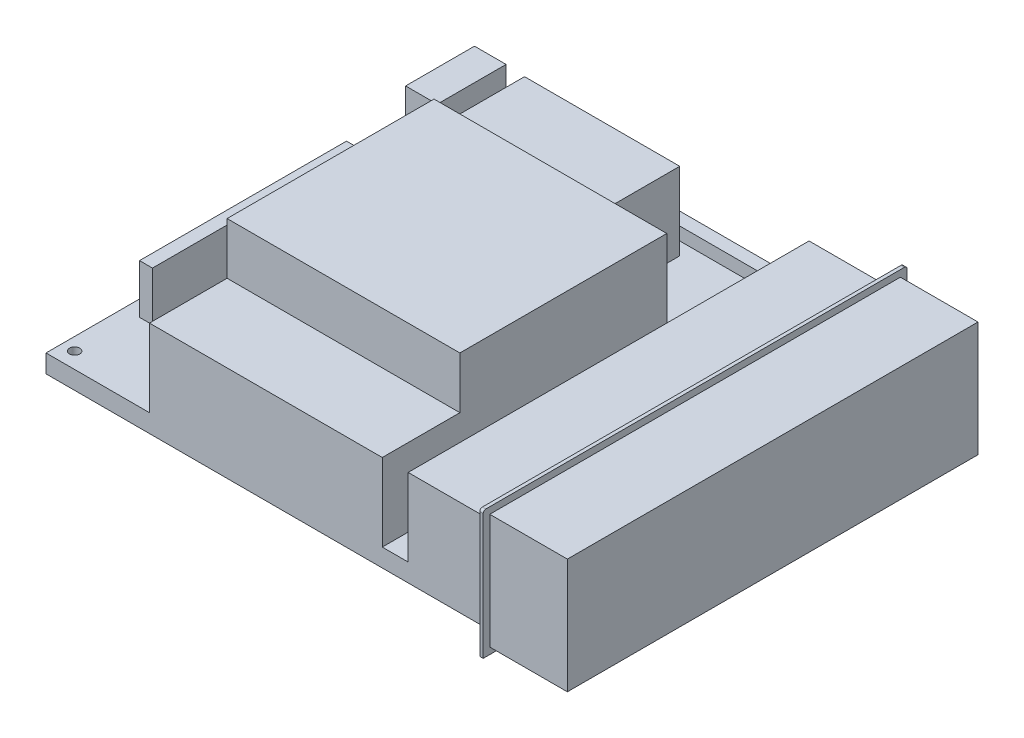
SolidWorks part; units mm, degrees
ref_plane "Front Plane" through (0, 0, 0) normal (0, 0, 1) x (1, 0, 0)
ref_plane "Top Plane" through (0, 0, 0) normal (0, 1, 0) x (1, 0, 0)
ref_plane "Right Plane" through (0, 0, 0) normal (1, 0, 0) x (0, 0, -1)
sketch "Sketch1" plane through (0, 0, 0) normal (0, 1, 0) x (1, 0, 0)
  line L1 (-85, -85) -> (85, -85)
  line L2 (-85, -85) -> (-85, 85)
  line L3 (-85, 85) -> (85, 85)
  line L4 (85, -85) -> (85, 85)
  line L5 (-85, -85) -> (85, 85) construction
  line L6 (-85, 85) -> (85, -85) construction
  point P0 (0, 0)
  dimension "D1" = 170
extrude "alusplaat" add sketch "Sketch1" along normal blind 2
sketch "Sketch2" plane through (0, 2, 0) normal (0, 1, 0) x (-1, 0, 0)
  line L1 (-85, 85) -> (-55, 85)
  line L2 (-85, 85) -> (-85, -70)
  line L3 (-85, -70) -> (-55, -70)
  line L4 (-55, 85) -> (-55, -70)
  dimension "D1" = 155
  dimension "D2" = 30
extrude "pistikud" add sketch "Sketch2" along normal blind 35
sketch "Sketch3" plane through (0, 2, 0) normal (0, 1, 0) x (1, 0, 0)
  line L0 (-85, -85) -> (55, -85) construction
  line L1 (-45, -85) -> (45, -85)
  line L2 (-45, -85) -> (-45, 25)
  line L3 (-45, 25) -> (45, 25)
  line L4 (45, -85) -> (45, 25)
  line L5 (-85, 85) -> (-85, -85) construction
  dimension "D1" = 90
  dimension "D2" = 40
  dimension "D3" = 110
extrude "cpu+mälud" add sketch "Sketch3" along normal blind 55
sketch "Sketch4" plane through (0, 2, 0) normal (0, 1, 0) x (1, 0, 0)
  line L1 (5, 35) -> (-55, 35)
  line L2 (5, 35) -> (5, 70)
  line L3 (5, 70) -> (-55, 70)
  line L4 (-55, 35) -> (-55, 70)
  line L5 (-85, 85) -> (-85, -85) construction
  line L6 (85, 85) -> (-85, 85) construction
  dimension "D1" = 35
  dimension "D2" = 60
  dimension "D3" = 30
  dimension "D4" = 15
extrude "sinine radikas" add sketch "Sketch4" along normal blind 35
sketch "Sketch5" plane through (0, 2, 0) normal (0, 1, 0) x (-1, 0, 0)
  line L0 (85, -85) -> (85, 85) construction
  line L1 (45, -75) -> (-45, -75)
  line L2 (45, -75) -> (45, -80)
  line L3 (45, -80) -> (-45, -80)
  line L4 (-45, -75) -> (-45, -80)
  line L5 (-85, -85) -> (85, -85) construction
  dimension "D1" = 90
  dimension "D2" = 40
  dimension "D3" = 5
  dimension "D4" = 5
extrude "pcie pesa" add sketch "Sketch5" along normal blind 10
sketch "Sketch6" plane through (0, 2, 0) normal (0, 1, 0) x (-1, 0, 0)
  line L1 (67.672, -48.9124) -> (79.8888, -48.9124)
  line L2 (67.672, -48.9124) -> (67.672, -75.5395)
  line L3 (67.672, -75.5395) -> (79.8888, -75.5395)
  line L4 (79.8888, -48.9124) -> (79.8888, -75.5395)
extrude "raid pesad" add sketch "Sketch6" along normal blind 30
sketch "Sketch7" plane through (0, 2, 0) normal (0, 1, 0) x (-1, 0, 0)
  line L1 (85, -85) -> (-85, -85)
  line L2 (85, -85) -> (85, 85)
  line L3 (85, 85) -> (-85, 85)
  line L4 (-85, -85) -> (-85, 85)
extrude "üleüldine müra" add sketch "Sketch7" along normal blind 5
sketch "Sketch8" plane through (0, 7, 0) normal (0, 1, 0) x (-1, 0, 0)
  line L0 (-85, -85) -> (85, -85) construction
  line L1 (78.8401, -25) -> (73.8401, -25)
  line L2 (78.8401, -25) -> (78.8401, 55)
  line L3 (78.8401, 55) -> (73.8401, 55)
  line L4 (73.8401, -25) -> (73.8401, 55)
  dimension "D1" = 5
  dimension "D2" = 80
  dimension "D3" = 60
extrude "patrei ja igasugused lülitid" add sketch "Sketch8" along normal blind 19
sketch "Sketch9" plane through (0, 57, 0) normal (0, 1, 0) x (-1, 0, 0)
  line L0 (-45, 85) -> (-45, -25) construction
  line L1 (45, -25) -> (-45, -25)
  line L2 (45, -25) -> (45, 55)
  line L3 (45, 55) -> (-45, 55)
  line L4 (-45, -25) -> (-45, 55)
  dimension "D1" = 80
extrude "mälud" cut sketch "Sketch9" against normal blind 20 flip side to cut
sketch "Sketch10" plane through (0, 7, 0) normal (0, 1, 0) x (1, 0, 0)
  line L0 (85, 85) -> (-85, 85) construction
  line L1 (74.84, 78.65) -> (-80.1, 78.65) construction
  line L2 (74.84, 78.65) -> (74.84, -78.83) construction
  line L3 (74.84, -78.83) -> (-80.1, -78.83) construction
  line L4 (-80.1, 78.65) -> (-80.1, -78.83) construction
  line L5 (85, 70) -> (85, 85) construction
  circle A0 centre (74.84, 78.65) radius 1.98
  circle A1 centre (-80.1, 78.65) radius 1.98
  circle A2 centre (-80.1, -78.83) radius 1.98
  circle A3 centre (51.98, -78.83) radius 1.98
  dimension "D6" = 3.96
  dimension "D1" = 6.35
  dimension "D2" = 10.16
  dimension "D3" = 154.94
  dimension "D4" = 157.48
  dimension "D5" = 22.86
extrude "Cut-Extrude2" cut sketch "Sketch10" against normal up to next
sketch "Sketch13" plane through (0, 7, 0) normal (0, 1, 0) x (1, 0, 0)
  line L1 (74.84, 78.65) -> (87.11, 78.65)
  line L2 (74.84, 78.65) -> (74.84, -92.9265)
  line L3 (74.84, -92.9265) -> (87.11, -92.9265)
  line L4 (87.11, 78.65) -> (87.11, -92.9265)
  dimension "D1" = 12.27
ref_plane "Plane2" through (87.11, 0, 0) normal (1, 0, 0) x (0, 0, -1)
sketch "Sketch11" plane through (87.11, 0, 0) normal (1, 0, 0) x (0, 0, -1)
  line L0 (-85, 0) -> (85, 0) construction
  line L1 (-86.875, -3.81) -> (71.875, -3.81) construction
  line L2 (-86.875, -3.81) -> (-86.875, 40.64) construction
  line L3 (-86.875, 40.64) -> (71.875, 40.64) construction
  line L4 (71.875, -3.81) -> (71.875, 40.64) construction
  line L5 (-88.415, 43.18) -> (73.415, 43.18)
  line L6 (71.875, 18.415) -> (70, 18.415) construction
  line L7 (70, 37) -> (70, 7) construction
  line L8 (-86.875, 18.415) -> (-85, 18.415) construction
  line L9 (-85, 37) -> (-85, 0) construction
  line L10 (74.415, -5.35) -> (74.415, 42.18)
  line L11 (-89.415, -6.35) -> (73.415, -6.35)
  line L12 (-89.415, -6.35) -> (-89.415, 42.18)
  line L13 (-89.415, -6.35) -> (74.415, -6.35) construction
  line L14 (74.415, -6.35) -> (74.415, 43.18) construction
  line L15 (-89.415, 43.18) -> (74.415, 43.18) construction
  line L16 (-89.415, -6.35) -> (-89.415, 43.18) construction
  arc A0 (73.415, -6.35) -> (74.415, -5.35) centre (73.415, -5.35) ccw
  arc A1 (74.415, 42.18) -> (73.415, 43.18) centre (73.415, 42.18) ccw
  arc A2 (-88.415, 43.18) -> (-89.415, 42.18) centre (-88.415, 42.18) ccw
  dimension "D5" = 1
  dimension "D1" = 158.75
  dimension "D2" = 44.45
  dimension "D3" = 3.81
  dimension "D4" = 2.54
extrude "Boss-Extrude1" add sketch "Sketch11" along normal blind 1.32
sketch "Sketch12" plane through (88.43, 0, 0) normal (1, 0, 0) x (0, 0, -1)
  line L1 (-86.875, -3.81) -> (71.875, -3.81)
  line L2 (-86.875, -3.81) -> (-86.875, 40.64)
  line L3 (-86.875, 40.64) -> (71.875, 40.64)
  line L4 (71.875, -3.81) -> (71.875, 40.64)
  line L5 (-88.415, 43.18) -> (73.415, 43.18)
  line L10 (74.415, -5.35) -> (74.415, 42.18)
  line L11 (-89.415, -6.35) -> (73.415, -6.35)
  line L12 (-89.415, -6.35) -> (-89.415, 42.18)
  line L13 (-89.415, -6.35) -> (74.415, -6.35) construction
  line L14 (74.415, -6.35) -> (74.415, 43.18) construction
  line L15 (-89.415, 43.18) -> (74.415, 43.18) construction
  line L16 (-89.415, -6.35) -> (-89.415, 43.18) construction
  arc A0 (73.415, -6.35) -> (74.415, -5.35) centre (73.415, -5.35) ccw
  arc A1 (74.415, 42.18) -> (73.415, 43.18) centre (73.415, 42.18) ccw
  arc A2 (-88.415, 43.18) -> (-89.415, 42.18) centre (-88.415, 42.18) ccw
  arc A5 (-88.415, 43.18) -> (-89.415, 42.18) centre (-88.415, 42.18) ccw construction
  dimension "D5" = 1
  dimension "D1" = 158.75
  dimension "D2" = 44.45
  dimension "D4" = 2.54
extrude "Boss-Extrude2" add sketch "Sketch12" along normal blind 30 contours L1 L4 L3 L2
